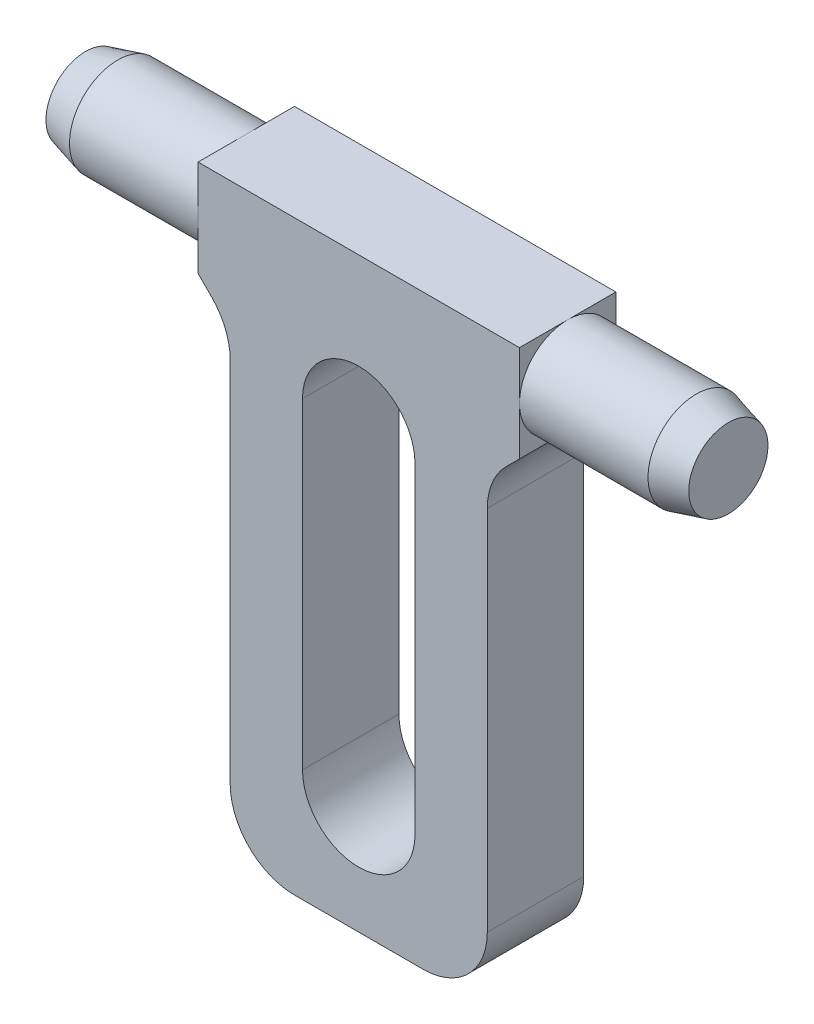
SolidWorks part; units mm, degrees
ref_plane "Plan de face" through (0, 0, 0) normal (0, 0, 1) x (1, 0, 0)
ref_plane "Plan de dessus" through (0, 0, 0) normal (0, 1, 0) x (1, 0, 0)
ref_plane "Plan de droite" through (0, 0, 0) normal (1, 0, 0) x (0, 0, -1)
sketch "Esquisse1" plane through (0, 0, 0) normal (0, 0, 1) x (1, 0, 0)
  line L0 (-5, -1.5) -> (-4.5858, -1.9142)
  line L1 (-5, 1.5) -> (5, 1.5)
  line L2 (-5, 1.5) -> (-5, -1.5)
  line L3 (-4, -3.3284) -> (-4, -14.75)
  line L4 (5, 1.5) -> (5, -1.5)
  line L5 (-5, 1.5) -> (5, -1.5) construction
  line L6 (-5, -1.5) -> (5, 1.5) construction
  line L7 (-2, -16.75) -> (2, -16.75)
  line L8 (4, -14.75) -> (4, -3.3284)
  line L9 (4.5858, -1.9142) -> (5, -1.5)
  line L10 (0, -3.25) -> (0, -13.25) construction
  line L11 (1.75, -3.25) -> (1.75, -13.25)
  line L12 (-4, -2.5) -> (4, -2.5) construction
  line L13 (4, -2.5) -> (0, 0) construction
  line L14 (0, 0) -> (-4, -2.5) construction
  line L15 (-1.75, -3.25) -> (-1.75, -13.25)
  line L16 (0, -13.25) -> (0, -16.75) construction
  line L17 (-1.75, -13.25) -> (1.75, -13.25) construction
  line L18 (-5, -1.5) -> (0, -1.5) construction
  arc A0 (1.75, -3.25) -> (-1.75, -3.25) centre (0, -3.25) ccw
  arc A1 (-1.75, -13.25) -> (1.75, -13.25) centre (0, -13.25) ccw
  arc A2 (4, -3.3284) -> (4.5858, -1.9142) centre (6, -3.3284) cw
  arc A3 (-4.5858, -1.9142) -> (-4, -3.3284) centre (-6, -3.3284) cw
  arc A4 (2, -16.75) -> (4, -14.75) centre (2, -14.75) ccw
  arc A5 (-4, -14.75) -> (-2, -16.75) centre (-2, -14.75) ccw
  point P0 (0, 0)
  point P13 (0, -8.25)
  dimension "D6" = 2
  dimension "D1" = 10
  dimension "D2" = 8
  dimension "D3" = 3
  dimension "D4" = 1
  dimension "D5" = 3.5
  dimension "D7" = 10
extrude "Boss.-Extru.1" add sketch "Esquisse1" along normal mid plane 3
sketch "Esquisse3" plane through (0, 0, 0) normal (1, 0, 0) x (0, 0, -1)
  circle A0 centre (0, 0) radius 1.5
  dimension "D1" = 3
extrude "Boss.-Extru.2" add sketch "Esquisse3" along normal mid plane 20
ref_axis "Axe1" through (11, 0, 0) along (-1, 0, 0)
sketch "Esquisse4" plane through (0, 0, 0) normal (0, 1, 0) x (1, 0, 0)
  line L0 (-10, 1.5) -> (-9, 1.5)
  line L1 (-5, 1.5) -> (-10, 1.5) construction
  line L2 (-9, 1.5) -> (-10, 1.2321)
  line L3 (-10, 1.5) -> (-10, -1.5) construction
  line L4 (-10, 1.2321) -> (-10, 1.5)
  line L5 (0, -1000) -> (0, 49000) construction
  line L6 (10, 1.2321) -> (10, 1.5)
  line L7 (9, 1.5) -> (10, 1.2321)
  line L8 (10, 1.5) -> (9, 1.5)
  dimension "D1" = 1
  dimension "D2" = 15
revolve "Enlèvement de matière-Révolution1" cut sketch "Esquisse4" angle 360 about axis through (11, 0, 0) along (-1, 0, 0)
